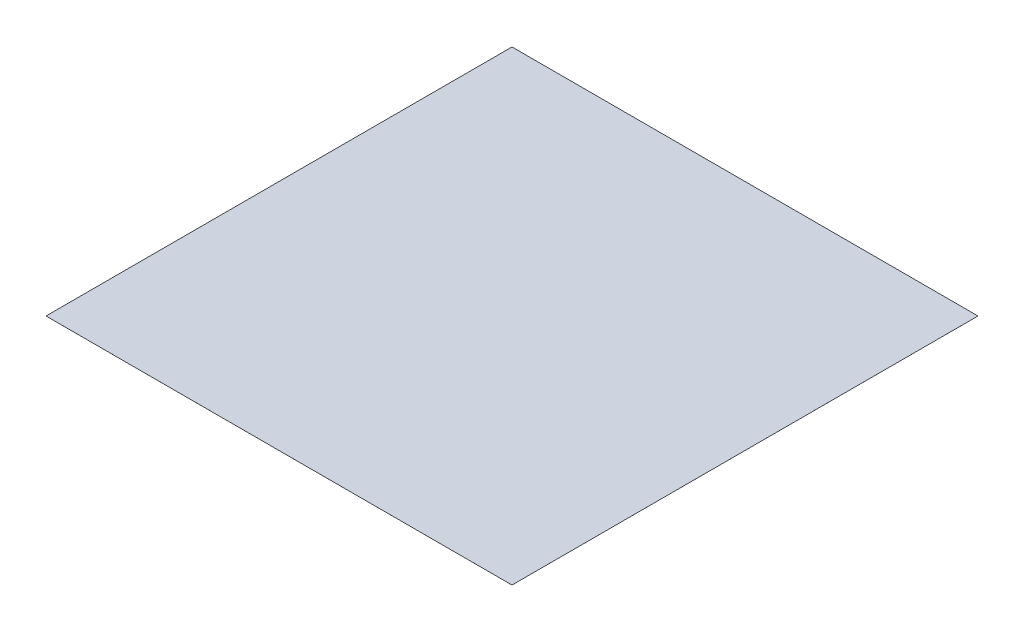
SolidWorks part; units mm, degrees
ref_plane "Plano frontal" through (0, 0, 0) normal (0, 0, 1) x (1, 0, 0)
ref_plane "Plano superior" through (0, 0, 0) normal (0, 1, 0) x (1, 0, 0)
ref_plane "Plano direito" through (0, 0, 0) normal (1, 0, 0) x (0, 0, -1)
sketch "Esboço1" plane through (0, 0, 0) normal (0, 1, 0) x (1, 0, 0)
  line L1 (-2632.9989, 3395.3214) -> (3067.0011, 3395.3214)
  line L2 (-2632.9989, 3395.3214) -> (-2632.9989, -2304.6786)
  line L3 (-2632.9989, -2304.6786) -> (3067.0011, -2304.6786)
  line L4 (3067.0011, 3395.3214) -> (3067.0011, -2304.6786)
extrude "Ressalto-extrusão1" add sketch "Esboço1" along normal blind 0.1
